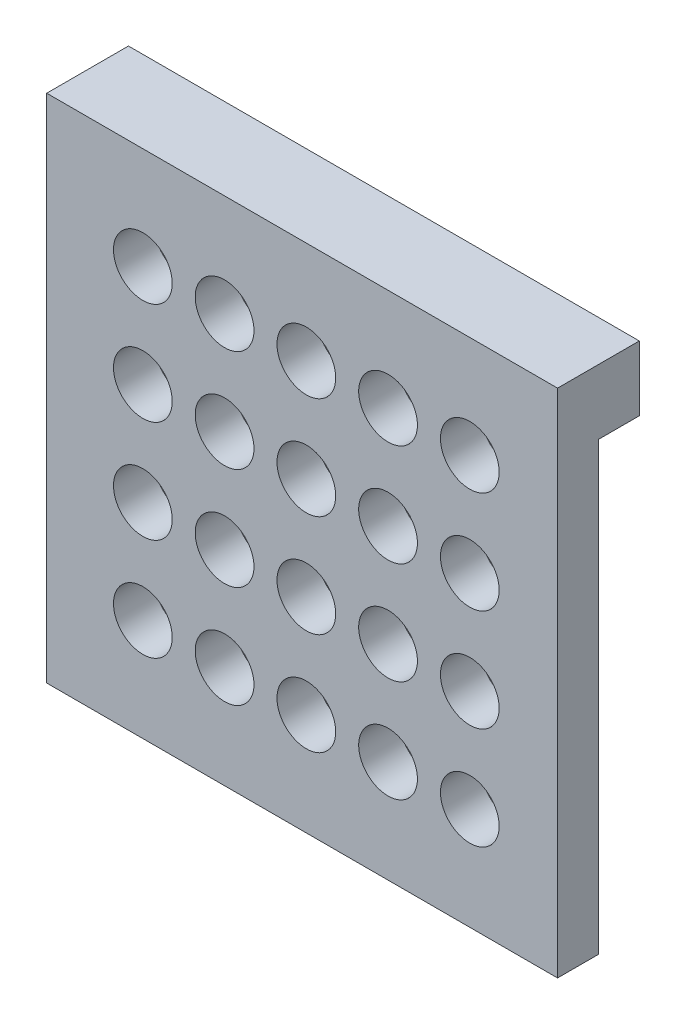
SolidWorks part; units mm, degrees
ref_plane "Ön Düzlem" through (0, 0, 0) normal (0, 0, 1) x (1, 0, 0)
ref_plane "Üst Düzlem" through (0, 0, 0) normal (0, 1, 0) x (1, 0, 0)
ref_plane "Sağ Düzlem" through (0, 0, 0) normal (1, 0, 0) x (0, 0, -1)
sketch "Sketch1" plane through (0, 0, 0) normal (0, 0, 1) x (1, 0, 0)
  line L1 (0, 0) -> (50, 0)
  line L2 (0, 0) -> (0, 50)
  line L3 (0, 50) -> (50, 50)
  line L4 (50, 0) -> (50, 50)
  dimension "D1" = 50
  dimension "D2" = 50
extrude "Boss-Extrude1" add sketch "Sketch1" along normal blind 4
sketch "Sketch2" plane through (0, 0, 4) normal (0, 0, 1) x (1, 0, 0)
  circle A0 centre (9.4109, 40.0098) radius 2.875
  circle A1 centre (17.4109, 40.0098) radius 2.875
  circle A2 centre (25.4109, 40.0098) radius 2.875
  circle A3 centre (33.4109, 40.0098) radius 2.875
  circle A4 centre (41.4109, 40.0098) radius 2.875
  circle A5 centre (17.4109, 30.0098) radius 2.875
  circle A6 centre (25.4109, 30.0098) radius 2.875
  circle A7 centre (33.4109, 30.0098) radius 2.875
  circle A8 centre (41.4109, 30.0098) radius 2.875
  circle A9 centre (17.4109, 20.0098) radius 2.875
  circle A10 centre (25.4109, 20.0098) radius 2.875
  circle A11 centre (33.4109, 20.0098) radius 2.875
  circle A12 centre (41.4109, 20.0098) radius 2.875
  circle A13 centre (17.4109, 10.0098) radius 2.875
  circle A14 centre (25.4109, 10.0098) radius 2.875
  circle A15 centre (33.4109, 10.0098) radius 2.875
  circle A16 centre (41.4109, 10.0098) radius 2.875
  circle A17 centre (9.4109, 30.0098) radius 2.875
  circle A18 centre (9.4109, 20.0098) radius 2.875
  circle A19 centre (9.4109, 10.0098) radius 2.875
  dimension "D1" = 5
  dimension "D2" = 4
extrude "Cut-Extrude1" cut sketch "Sketch2" against normal blind 4
sketch "Sketch3" plane through (0, 0, 0) normal (0, 0, -1) x (-1, 0, 0)
  line L0 (0, 50) -> (0, 0) construction
  line L1 (-50, 50) -> (0, 50)
  line L2 (-50, 50) -> (-50, 43.6517)
  line L3 (-50, 43.6517) -> (0, 43.6517)
  line L4 (0, 50) -> (0, 43.6517)
extrude "Boss-Extrude2" add sketch "Sketch3" along normal blind 4
